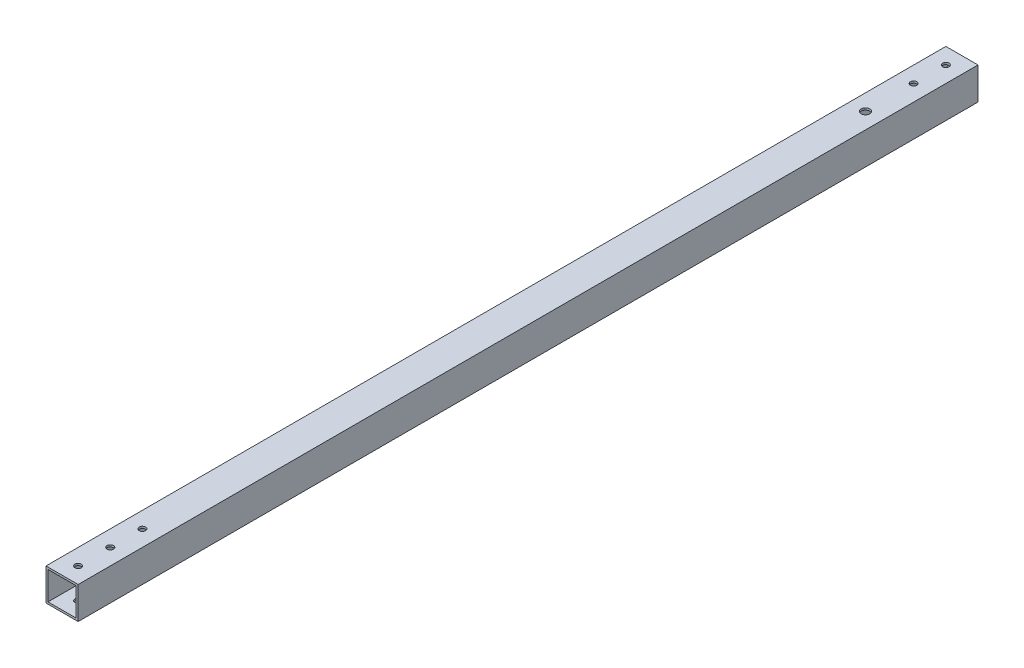
SolidWorks part; units mm, degrees
ref_plane "Front Plane" through (0, 0, 0) normal (0, 0, 1) x (1, 0, 0)
ref_plane "Top Plane" through (0, 0, 0) normal (0, 1, 0) x (1, 0, 0)
ref_plane "Right Plane" through (0, 0, 0) normal (1, 0, 0) x (0, 0, -1)
sketch "Sketch1" plane through (0, 0, 0) normal (0, 0, 1) x (1, 0, 0)
  line L1 (0, 0) -> (25.4, 0)
  line L2 (0, 0) -> (0, 25.4)
  line L3 (0, 25.4) -> (25.4, 25.4)
  line L4 (25.4, 0) -> (25.4, 25.4)
  line L5 (1.5875, 1.5875) -> (23.8125, 1.5875)
  line L6 (1.5875, 1.5875) -> (1.5875, 23.8125)
  line L7 (1.5875, 23.8125) -> (23.8125, 23.8125)
  line L8 (23.8125, 1.5875) -> (23.8125, 23.8125)
  dimension "D1" = 25.4
  dimension "D2" = 1.5875
  dimension "D3" = 1.5875
  dimension "D4" = 1.5875
  dimension "D5" = 1.5875
extrude "Boss-Extrude1" add sketch "Sketch1" along normal blind 711.2
sketch "Sketch2" plane through (25.4, 0, 0) normal (1, 0, 0) x (0, 0, -1)
  line L0 (-711.2, 0) -> (-711.2, 25.4) construction
  line L1 (-711.2, 25.4) -> (0, 25.4) construction
  circle A0 centre (-698.5, 12.7) radius 6.35
  dimension "D2" = 12.7
  dimension "D1" = 12.7
  dimension "D3" = 12.7
sketch "Sketch3" plane through (0, 25.4, 0) normal (0, 1, 0) x (1, 0, 0)
  line L2 (25.4, 0) -> (0, 0) construction
  line L3 (0, -711.2) -> (0, 0) construction
  line L4 (25.4, -711.2) -> (0, -711.2) construction
  circle A1 centre (12.7, -12.7) radius 2.54
  circle A4 centre (12.7, -698.5) radius 2.54
  circle A5 centre (12.7, -38.1) radius 2.54
  circle A6 centre (12.7, -673.1) radius 2.54
  circle A7 centre (12.7, -647.7) radius 2.54
  circle A8 centre (12.7, -76.2) radius 3.429
  dimension "D3" = 5.08
  dimension "D6" = 6.858
  dimension "D1" = 12.7
  dimension "D2" = 12.7
  dimension "D4" = 12.7
  dimension "D5" = 3
  dimension "D7" = 38.1
  dimension "1" = 25.4
extrude "Cut-Extrude2" cut sketch "Sketch3" against normal through all
